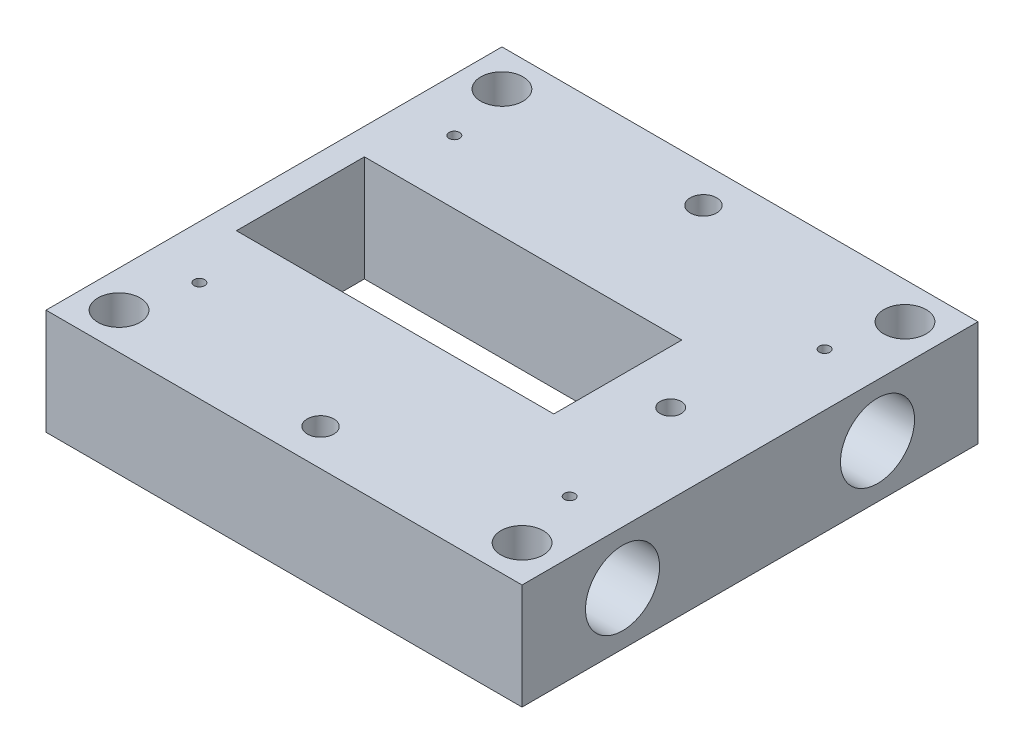
SolidWorks part; units mm, degrees
ref_plane "Front Plane" through (0, 0, 0) normal (0, 0, 1) x (1, 0, 0)
ref_plane "Top Plane" through (0, 0, 0) normal (0, 1, 0) x (1, 0, 0)
ref_plane "Right Plane" through (0, 0, 0) normal (1, 0, 0) x (0, 0, -1)
sketch "Sketch2" plane through (0, 0, 0) normal (1, 0, 0) x (0, 0, -1)
  line L0 (-24.1, 0) -> (24.1, 0) construction
  line L5 (-38.1, 0) -> (38.1, 0) construction
  line L6 (-43.1, -10) -> (43.1, -10)
  line L7 (-43.1, -10) -> (-43.1, 10)
  line L8 (-43.1, 10) -> (43.1, 10)
  line L9 (43.1, -10) -> (43.1, 10)
  line L10 (-43.1, -10) -> (43.1, 10) construction
  line L11 (-43.1, 10) -> (43.1, -10) construction
  circle A0 centre (-24.1, 0) radius 7
  circle A1 centre (24.1, 0) radius 7
  point P4 (0, 0)
  point P6 (0, 0)
  point P12 (-24.1, 7)
  point P14 (-31.1, 0)
  dimension "D1" = 14
  dimension "D2" = 3
  dimension "D3" = 76.2
  dimension "D4" = 5
  dimension "D5" = 7
extrude "Boss-Extrude1" add sketch "Sketch2" along normal mid plane 90
sketch "Sketch3" plane through (0, -10, 0) normal (0, -1, 0) x (1, 0, 0)
  line L1 (-38.1, -36.195) -> (38.1, -36.195) construction
  line L2 (-38.1, -36.195) -> (-38.1, 36.195) construction
  line L3 (-38.1, 36.195) -> (38.1, 36.195) construction
  line L4 (38.1, -36.195) -> (38.1, 36.195) construction
  line L5 (-38.1, -36.195) -> (38.1, 36.195) construction
  line L6 (-38.1, 36.195) -> (38.1, -36.195) construction
  circle A0 centre (-38.1, 36.195) radius 1.375
  circle A1 centre (38.1, 36.195) radius 1.375
  circle A2 centre (38.1, -36.195) radius 1.375
  circle A3 centre (-38.1, -36.195) radius 1.375
  point P0 (0, 0)
  dimension "D3" = 2.75
  dimension "D1" = 72.39
  dimension "D2" = 76.2
extrude "Cut-Extrude1" cut sketch "Sketch3" against normal through all
sketch "Sketch4" plane through (0, 10, 0) normal (0, 1, 0) x (1, 0, 0)
  circle A0 centre (-38.1, -36.195) radius 4
  circle A1 centre (-38.1, 36.195) radius 4
  circle A2 centre (38.1, 36.195) radius 4
  circle A3 centre (38.1, -36.195) radius 4
  dimension "D1" = 8
extrude "Cut-Extrude2" cut sketch "Sketch4" against normal offset from surface (17 mm away) 3 up to face at (-38.1, -10, -37.57)
sketch "Sketch5" plane through (0, 0, 0) normal (1, 0, 0) x (0, 0, -1)
  circle A0 centre (24.1, 0) radius 7 construction
  circle A1 centre (-24.1, 0) radius 7 construction
  circle A2 centre (24.1, 0) radius 7
  circle A3 centre (-24.1, 0) radius 7
  circle A4 centre (-24.1, 0) radius 5
  circle A5 centre (24.1, 0) radius 5
  dimension "D1" = 10
extrude "Boss-Extrude2" add sketch "Sketch5" along normal mid plane 42
sketch "Sketch6" plane through (0, 10, 0) normal (0, 1, 0) x (1, 0, 0)
  line L0 (45, 43.1) -> (45, -43.1) construction
  circle A0 centre (30, 0) radius 2
  circle A1 centre (0, -36.195) radius 2.5
  circle A2 centre (0, 36.195) radius 2.5
  circle A3 centre (-38.1, -36.195) radius 1.375 construction
  circle A4 centre (-38.1, -36.195) radius 1.375 construction
  circle A5 centre (-38.1, 36.195) radius 1.375 construction
  circle A6 centre (-38.1, 36.195) radius 1.375 construction
  point P10 (0, 0)
  point P11 (0, 0)
  point P18 (0, 0)
  point P19 (0, 0)
  dimension "D1" = 4
  dimension "D3" = 5
  dimension "D2" = 15
extrude "Cut-Extrude3" cut sketch "Sketch6" against normal through all
sketch "Sketch7" plane through (0, -10, 0) normal (0, -1, 0) x (1, 0, 0)
  circle A0 centre (30, 0) radius 5
  circle A1 centre (0, 36.195) radius 5
  circle A2 centre (0, -36.195) radius 5
  dimension "D1" = 10
extrude "Cut-Extrude4" cut sketch "Sketch7" against normal offset from surface (16 mm away) 4 up to face at (30, 10, 2)
sketch "Sketch8" plane through (0, 10, 0) normal (0, 1, 0) x (1, 0, 0)
  line L0 (45, -31.1) -> (45, -17.1) construction
  line L1 (35, 24.1) -> (-35, 24.1) construction
  line L2 (35, 24.1) -> (35, -24.1) construction
  line L3 (35, -24.1) -> (-35, -24.1) construction
  line L4 (-35, 24.1) -> (-35, -24.1) construction
  line L5 (35, 24.1) -> (-35, -24.1) construction
  line L6 (35, -24.1) -> (-35, 24.1) construction
  line L7 (45, -31.1) -> (45, -17.1) construction
  line L8 (45, 43.1) -> (45, -43.1) construction
  circle A0 centre (35, -24.1) radius 1
  circle A1 centre (-35, -24.1) radius 1
  circle A2 centre (-35, 24.1) radius 1
  circle A3 centre (35, 24.1) radius 1
  point P0 (0, 0)
  point P8 (45, -24.1)
  dimension "D2" = 2
  dimension "D1" = 10
extrude "Cut-Extrude5" cut sketch "Sketch8" against normal up to next
sketch "Sketch9" plane through (0, 10, 0) normal (0, 1, 0) x (1, 0, 0)
  line L0 (-21, -17.1) -> (-45, -17.1) construction
  line L1 (20, -12.1) -> (-40, -12.1)
  line L2 (20, -12.1) -> (20, 12.1)
  line L3 (20, 12.1) -> (-40, 12.1)
  line L4 (-40, -12.1) -> (-40, 12.1)
  line L5 (20, -12.1) -> (-40, 12.1) construction
  line L6 (20, 12.1) -> (-40, -12.1) construction
  line L7 (-45, 43.1) -> (-45, -43.1) construction
  circle A0 centre (30, 0) radius 5 construction
  circle A1 centre (30, 0) radius 2 construction
  circle A2 centre (30, 0) radius 2 construction
  point P0 (-10, 0)
  point P5 (0, 0)
  point P12 (25, 0)
  point P18 (0, 0)
  dimension "D1" = 5
  dimension "D2" = 5
  dimension "D3" = 5
extrude "Cut-Extrude6" cut sketch "Sketch9" against normal through all
